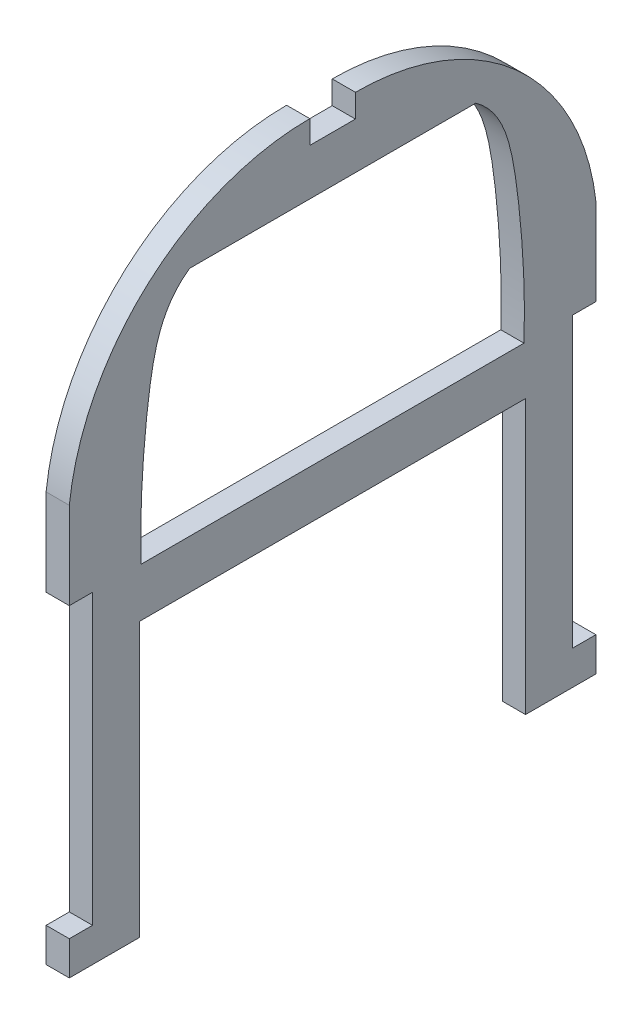
SolidWorks part; units mm, degrees
ref_plane "Front Plane" through (0, 0, 0) normal (0, 0, 1) x (1, 0, 0)
ref_plane "Top Plane" through (0, 0, 0) normal (0, 1, 0) x (1, 0, 0)
ref_plane "Right Plane" through (0, 0, 0) normal (1, 0, 0) x (0, 0, -1)
sketch "Sketch1" plane through (0, 0, 0) normal (1, 0, 0) x (0, 0, -1)
  line L0 (-24.75, 0) -> (24.75, 0)
  line L1 (0, 0) -> (0, 30)
  line L2 (-18.5, 30) -> (18.5, 30)
  line L3 (0, 30) -> (0, 36)
  line L4 (-2.95, 36) -> (2.95, 36)
  line L5 (2.95, 36) -> (2.95, 39)
  line L6 (24.75, 0) -> (34.05, 0)
  line L7 (34.05, 0) -> (34.05, 11.2451)
  line L8 (34.05, 0) -> (31.05, 0)
  line L9 (31.05, 0) -> (31.05, -37.3)
  line L10 (31.05, -37.3) -> (34.05, -37.3)
  line L11 (34.05, -37.3) -> (34.05, -41.7)
  line L12 (34.05, -41.7) -> (24.95, -41.7)
  line L13 (24.95, -41.7) -> (24.95, -6.3)
  line L14 (24.95, -6.3) -> (-24.95, -6.3)
  line L15 (0, -6.3) -> (0, 0)
  line L16 (-24.95, -41.7) -> (-24.95, -6.3)
  line L17 (-34.05, -41.7) -> (-24.95, -41.7)
  line L18 (-34.05, -37.3) -> (-34.05, -41.7)
  line L19 (-31.05, -37.3) -> (-34.05, -37.3)
  line L20 (-31.05, 0) -> (-31.05, -37.3)
  line L21 (-34.05, 0) -> (-31.05, 0)
  line L22 (-34.05, 0) -> (-34.05, 11.2451)
  line L23 (-24.75, 0) -> (-34.05, 0)
  line L24 (-2.95, 36) -> (-2.95, 39)
  arc A0 (2.95, 39) -> (34.05, 11.2451) centre (2.95, 7.6984) cw
  arc A1 (-2.95, 39) -> (-34.05, 11.2451) centre (-2.95, 7.6984) ccw
  spline S0 degree 3 poles (18.5, 30) (21.8999, 27.6228) (23.3386, 22.0645) (24.6033, 11.6889) (24.929, 4.972) (24.75, 0) knots 0 0 0 0 0.363582 0.525535 1 1 1 1
  spline S1 degree 3 poles (-18.5, 30) (-21.8999, 27.6228) (-23.3386, 22.0645) (-24.6033, 11.6889) (-24.929, 4.972) (-24.75, 0) knots 0 0 0 0 0.363582 0.525535 1 1 1 1
  point P4 (0, 0)
  point P10 (0, 30)
  point P14 (0, 36)
  dimension "D1" = 49.5
  dimension "D2" = 30
  dimension "D3" = 37
  dimension "D4" = 6
  dimension "D5" = 5.9
  dimension "D6" = 3
  dimension "D7" = 9.3
  dimension "D8" = 3
  dimension "D9" = 37.3
  dimension "D10" = 4.4
  dimension "D11" = 3
  dimension "D12" = 9.1
  dimension "D13" = 6.3
extrude "Boss-Extrude1" add sketch "Sketch1" along normal blind 3 contours S1 L2 L3 L4 L24 A1 L22 L21 L23 | L2 S0 L6 L7 A0 L5 L4 L3 | L15 L14 L13 L12 L11 L10 L9 L6 L0 | L0 L23 L20 L19 L18 L17 L16 L14 L15
